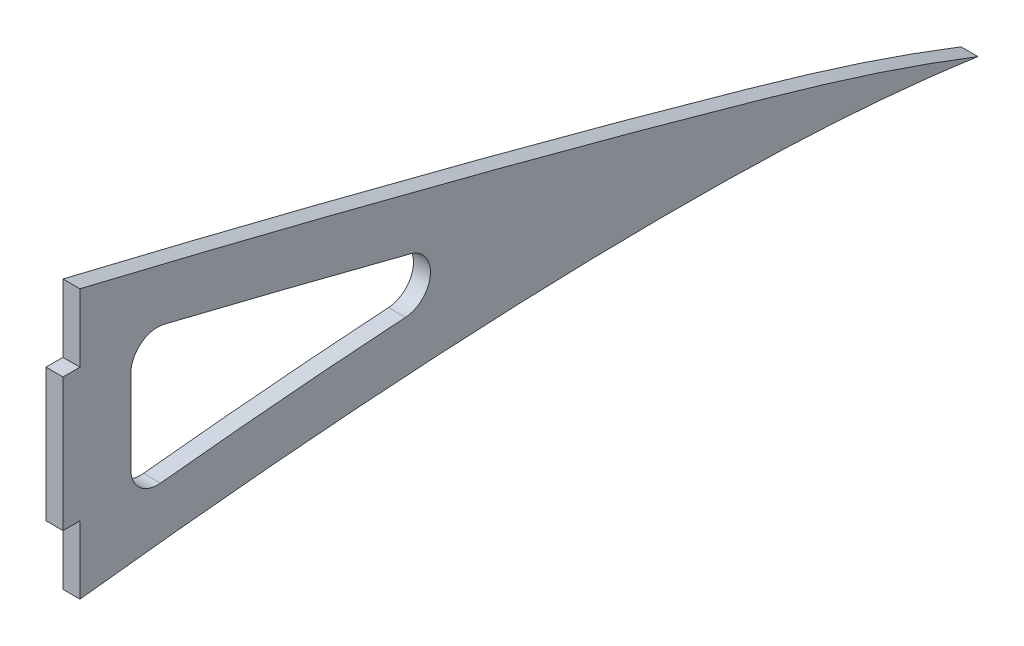
SolidWorks part; units mm, degrees
material "Balsa"
ref_plane "Front" through (0, 0, 0) normal (0, 0, 1) x (1, 0, 0)
ref_plane "Top" through (0, 0, 0) normal (0, 1, 0) x (1, 0, 0)
ref_plane "Right" through (0, 0, 0) normal (1, 0, 0) x (0, 0, -1)
sketch "Sketch1" plane through (0, 0, 0) normal (1, 0, 0) x (0, 0, -1)
  line L0 (616.0961, 24.8993) -> (616.0961, 10.6118) construction
  line L1 (616.0961, 24.8993) -> (616.0961, 10.5667)
  line L2 (612.9211, 24.8993) -> (612.9211, 10.6118) construction
  line L3 (616.0961, 10.5667) -> (612.9211, 10.5667)
  line L4 (616.0961, -14.3323) -> (612.9211, -14.3323)
  line L5 (616.0961, 23.2667) -> (616.0961, 10.5667) construction
  line L6 (616.0961, -27.0323) -> (616.0961, -14.3323)
  line L7 (612.9211, 10.5667) -> (612.9211, -14.3323)
  spline S0 degree 3 poles (304.4894, -1963.048) (904.56, -11.0089) (840.5576, -43.532) (789.3572, -23.4586) (777.0615, -18.6436) (760.5817, -13.0401) (739.9968, -7.1233) (715.5772, -0.3798) (687.647, 7.013) (656.6835, 14.9584) (623.1589, 23.2583) (587.5492, 31.6944) (550.3192, 40.0262) (511.9148, 48.0016) (472.7617, 55.3745) (433.2622, 61.9128) (393.7959, 67.4048) (354.7199, 71.6552) (316.357, 74.5357) (278.9313, 75.7536) (242.6994, 75.3938) (207.8706, 73.5467) (174.7468, 70.259) (143.6014, 65.7682) (114.7621, 60.1875) (88.5345, 53.6285) (65.199, 46.2382) (45.0006, 38.1339) (28.1586, 29.5092) (14.871, 20.5578) (6.1442, 12.3133) (1.9481, 6.1765) (0.6391, 3.0841) (0.217, 1.668) (-2.2377, -10.856) (31.8726, -26.5577) (-1993.0578, 155.2139) knots -0.166991 -0.166991 -0.166991 -0.166991 0.003802 0.014472 0.030564 0.051299 0.077028 0.107574 0.142399 0.180921 0.222525 0.266591 0.312515 0.35971 0.407632 0.455773 0.503669 0.550901 0.597096 0.641976 0.685512 0.727353 0.767354 0.805169 0.840471 0.872937 0.902335 0.928425 0.951113 0.970253 0.985871 0.993982 0.996753 0.997907 0.999293 1.04244 1.04244 1.04244 1.04244 only from (802.1511, -28.0117) to (0, 0) construction
  spline S1 degree 3 poles (802.1511, -28.0117) (801.1372, -27.7105) (797.2784, -26.5642) (789.3572, -23.4586) (777.0615, -18.6436) (760.5817, -13.0401) (739.9968, -7.1233) (715.5772, -0.3798) (687.647, 7.013) (656.6835, 14.9584) (623.1589, 23.2583) (587.5492, 31.6944) (550.3192, 40.0262) (511.9148, 48.0016) (472.7617, 55.3745) (433.2622, 61.9128) (393.7959, 67.4048) (354.7199, 71.6552) (316.357, 74.5357) (278.9313, 75.7536) (242.6994, 75.3938) (207.8706, 73.5467) (174.7468, 70.259) (143.6014, 65.7682) (114.7621, 60.1875) (88.5345, 53.6285) (65.199, 46.2382) (45.0006, 38.1339) (28.1586, 29.5092) (14.871, 20.5578) (6.1442, 12.3133) (1.9481, 6.1765) (0.6391, 3.0841) (0.217, 1.668) (0.0426, 0.7778) (0.0107, 0.1963) (0, 0) knots 0 0 0 0 0.003802 0.014472 0.030564 0.051299 0.077028 0.107574 0.142399 0.180921 0.222525 0.266591 0.312515 0.35971 0.407632 0.455773 0.503669 0.550901 0.597096 0.641976 0.685512 0.727353 0.767354 0.805169 0.840471 0.872937 0.902335 0.928425 0.951113 0.970253 0.985871 0.993982 0.996753 0.997907 0.999293 1 1 1 1
  spline S2 degree 3 poles (-1994.7901, -130.8385) (49.5083, 45.0487) (-3.9103, 18.1854) (0.5702, -4.3968) (2.5361, -10.6164) (7.9982, -20.5501) (16.1137, -34.185) (25.7513, -48.9002) (36.932, -62.9388) (49.3364, -75.9186) (65.2269, -85.625) (84.4528, -91.7174) (106.8521, -96.1515) (132.5109, -98.5722) (161.1944, -99.0924) (192.7613, -97.7042) (227.0382, -94.5118) (263.8348, -89.6638) (302.9215, -83.3884) (344.0178, -75.9778) (386.7768, -67.7807) (430.7746, -59.2023) (475.4963, -50.6638) (520.3353, -42.6036) (564.5889, -35.4228) (607.4709, -29.4733) (648.1275, -25.0145) (685.6676, -22.1862) (719.1968, -21.0048) (747.8303, -21.2786) (770.6884, -22.8547) (787.0914, -25.0735) (855.7552, -37.3672) (910.4178, -89.1553) (1388.6423, 1880.9845) knots -0.071347 -0.071347 -0.071347 -0.071347 0.001821 0.004613 0.009135 0.024676 0.044153 0.064937 0.086321 0.107138 0.1276 0.150893 0.177565 0.207668 0.241222 0.278203 0.318526 0.362031 0.408465 0.457479 0.508614 0.561296 0.614835 0.668438 0.721214 0.772202 0.820393 0.864766 0.904324 0.938132 0.965242 0.98469 0.99621 1.210002 1.210002 1.210002 1.210002 only from (0, 0) to (802.1511, -28.0117) construction
  spline S3 degree 3 poles (0, 0) (0.0175, -0.519) (0.0617, -1.8338) (0.5702, -4.3968) (2.5361, -10.6164) (7.9982, -20.5501) (16.1137, -34.185) (25.7513, -48.9002) (36.932, -62.9388) (49.3364, -75.9186) (65.2269, -85.625) (84.4528, -91.7174) (106.8521, -96.1515) (132.5109, -98.5722) (161.1944, -99.0924) (192.7613, -97.7042) (227.0382, -94.5118) (263.8348, -89.6638) (302.9215, -83.3884) (344.0178, -75.9778) (386.7768, -67.7807) (430.7746, -59.2023) (475.4963, -50.6638) (520.3353, -42.6036) (564.5889, -35.4228) (607.4709, -29.4733) (648.1275, -25.0145) (685.6676, -22.1862) (719.1968, -21.0048) (747.8303, -21.2786) (770.6884, -22.8547) (787.0914, -25.0735) (796.8423, -26.8193) (801.0977, -27.7751) (802.1511, -28.0117) knots 0 0 0 0 0.001821 0.004613 0.009135 0.024676 0.044153 0.064937 0.086321 0.107138 0.1276 0.150893 0.177565 0.207668 0.241222 0.278203 0.318526 0.362031 0.408465 0.457479 0.508614 0.561296 0.614835 0.668438 0.721214 0.772202 0.820393 0.864766 0.904324 0.938132 0.965242 0.98469 0.99621 1 1 1 1
  spline S4 degree 1 poles (784.1065, -23.1184) (1.589, -0.0169) knots 0 0 1 1 construction
  spline S5 degree 1 poles (1.589, -0.0169) (784.1065, -23.1184) knots 0 0 1 1 construction
  spline S6 degree 3 poles (784.1065, -23.1184) (780.1603, -21.5942) (772.229, -18.642) (760.1745, -14.6722) (747.9911, -11.0613) (731.6457, -6.456) (711.1768, -0.8453) (679.559, 7.4876) (651.9836, 14.4996) (624.3549, 21.2911) (606.6048, 25.5547) (576.4242, 32.5965) (537.8777, 41.1375) (487.9189, 51.0912) (437.7208, 59.724) (387.2787, 66.7289) (345.0506, 70.936) (311.1879, 73.0641) (277.2796, 74.2092) (243.3427, 73.88) (209.4764, 71.9586) (184.1438, 69.6475) (158.905, 66.4678) (133.8072, 62.3586) (108.9155, 57.1874) (88.425, 51.8354) (72.2738, 46.7811) (60.3184, 42.5401) (48.5771, 37.7737) (37.1197, 32.3878) (27.9272, 27.2538) (20.9064, 22.6554) (15.8717, 18.9075) (11.1186, 14.8241) (7.5582, 11.0807) (5.0251, 7.8349) (3.3892, 5.2955) (2.3111, 3.0614) (1.8056, 1.4859) (1.654, 0.7258) (1.6104, 0.3499) (1.5955, 0.1003) (1.589, -0.0169) knots 0.0223 0.0223 0.0223 0.0223 0.037575 0.05285 0.068125 0.083401 0.113951 0.144502 0.201029 0.216305 0.246855 0.266703 0.327804 0.388905 0.450006 0.511107 0.572208 0.602759 0.633309 0.69441 0.724961 0.755511 0.786062 0.816612 0.847162 0.877713 0.892988 0.908263 0.923539 0.938814 0.954089 0.961727 0.969364 0.977002 0.98464 0.988458 0.992277 0.996096 0.998005 0.99896 0.999438 0.999915 0.999915 0.999915 0.999915
  spline S7 degree 3 poles (1.589, -0.0169) (1.5978, -0.2781) (1.617, -0.8171) (1.6706, -1.5251) (1.7727, -2.2395) (1.9645, -3.217) (2.2822, -4.4731) (2.892, -6.4557) (3.825, -8.9127) (5.5748, -12.7649) (8.1549, -17.4947) (12.5101, -25.0363) (18.1123, -34.2943) (25.2301, -45.181) (31.6891, -53.8227) (37.2128, -60.4726) (42.9501, -66.9629) (50.6018, -74.4394) (61.3489, -81.5128) (73.1594, -86.5673) (85.641, -90.1112) (98.3223, -92.8576) (115.4237, -95.4885) (137.057, -97.1574) (163.0971, -97.3914) (189.1354, -96.2564) (215.1195, -94.0861) (241.0338, -91.1098) (275.4921, -86.3076) (318.4041, -79.1225) (369.7356, -69.4844) (421.0135, -59.4768) (472.335, -49.6151) (523.7845, -40.3589) (567.397, -33.4142) (602.5248, -28.6193) (637.1568, -24.5175) (671.3273, -21.4749) (705.604, -19.8163) (731.789, -19.4122) (758.0003, -20.1502) (775.4469, -21.8673) (784.1065, -23.1184) knots 0.000082 0.000082 0.000082 0.000082 0.001038 0.001993 0.002948 0.003903 0.005814 0.007724 0.011545 0.015366 0.023009 0.030651 0.045935 0.061219 0.076503 0.084145 0.091787 0.107071 0.122355 0.137639 0.152923 0.168208 0.183492 0.21406 0.244628 0.275196 0.305765 0.336333 0.366901 0.428038 0.489174 0.55031 0.611447 0.672583 0.73372 0.766342 0.79691 0.855993 0.886561 0.917129 0.947697 0.978266 0.978266 0.978266 0.978266
  point P8 (625.6211, 24.8993)
  point P9 (625.6211, -28.6308)
  dimension "D2" = 12.7
  dimension "D3" = 12.7
  dimension "D1" = 1.5875
extrude "Boss-Extrude1" add sketch "Sketch1" along normal mid plane 3.175 contours L6 S7 S6 L1 L3 L7 L4
sketch "Sketch3" plane through (-1.5875, 0, 0) normal (-1, 0, 0) x (0, 0, 1)
  line L8 (-616.0961, 10.5667) -> (-616.0961, -14.3323)
  line L10 (-625.6211, 10.5667) -> (-625.6211, -14.3323)
  line L12 (-625.6211, -16.3575) -> (-625.6211, -14.3323)
  line L14 (-625.6211, 10.5667) -> (-625.6211, 11.1624)
  line L22 (-616.0961, -27.0323) -> (-616.0961, -14.3323)
  line L23 (-616.0961, -14.3323) -> (-612.9211, -14.3323)
  line L24 (-612.9211, -14.3323) -> (-612.9211, 10.5667)
  line L25 (-612.9211, 10.5667) -> (-616.0961, 10.5667)
  line L26 (-616.0961, 10.5667) -> (-616.0961, 23.2667)
  line L27 (-616.0961, -27.0323) -> (-616.0961, -14.3323)
  line L31 (-616.0961, 10.5667) -> (-616.0961, 23.2667)
  spline S0 degree 1 poles (-709.5538, -10.3156) (-625.6211, -16.3575) knots 0 0 1 1 construction
  spline S1 degree 1 poles (-625.6211, 11.1624) (-709.5538, -10.3156) knots 0 0 1 1 construction
  spline S2 degree 3 poles (1634.6736, -1607.9777) (681.5883, 157.0929) (1.6305, 175.1672) (-651.9836, 14.4996) (-679.559, 7.4876) (-711.1768, -0.8453) (-731.6457, -6.456) (-747.9911, -11.0613) (-760.1745, -14.6722) (-967.9627, -83.1024) (-1104.2081, -346.6774) (-2002.5645, 2676.6356) knots -2.312001 -2.312001 -2.312001 -2.312001 0.037575 0.05285 0.109378 0.139928 0.170479 0.185754 0.201029 0.216305 0.97567 0.97567 0.97567 0.97567 only from (-616.0961, 23.2667) to (-784.1065, -23.1184)
  spline S3 degree 3 poles (-137.9126, -2890.9442) (-1254.9723, -306.121) (-1000.8122, -26.9869) (-731.789, -19.4122) (-705.604, -19.8163) (-671.3273, -21.4749) (-68.1702, -75.1819) (477.5748, -530.0036) (1018.4617, 2058.6772) knots -0.067892 -0.067892 -0.067892 -0.067892 0.812194 0.842762 0.87333 0.903899 0.962981 2.995374 2.995374 2.995374 2.995374 only from (-784.1065, -23.1184) to (-616.0961, -27.0323)
  spline S4 degree 3 poles (-616.0961, 23.2667) (-620.2246, 22.2755) (-628.4782, 20.2775) (-651.9836, 14.4996) (-679.559, 7.4876) (-711.1768, -0.8453) (-731.6457, -6.456) (-747.9911, -11.0613) (-760.1745, -14.6722) (-772.229, -18.642) (-780.1603, -21.5942) (-784.1065, -23.1184) knots 0.0223 0.0223 0.0223 0.0223 0.037575 0.05285 0.109378 0.139928 0.170479 0.185754 0.201029 0.216305 0.23158 0.23158 0.23158 0.23158
  spline S5 degree 3 poles (-784.1065, -23.1184) (-775.4469, -21.8673) (-758.0003, -20.1502) (-731.789, -19.4122) (-705.604, -19.8163) (-671.3273, -21.4749) (-641.5011, -24.1307) (-620.4251, -26.521) (-616.0961, -27.0323) knots 0.781626 0.781626 0.781626 0.781626 0.812194 0.842762 0.87333 0.903899 0.962981 0.978266 0.978266 0.978266 0.978266
  spline S6 degree 3 poles (-625.6211, -16.3575) (-632.5784, -15.5905) (-646.4983, -14.1649) (-667.4549, -12.4003) (-688.4629, -11.0653) (-702.5252, -10.5017) (-709.5538, -10.3156) knots 0.868429 0.868429 0.868429 0.868429 0.89278 0.917131 0.941482 0.965833 0.965833 0.965833 0.965833
  spline S7 degree 3 poles (-709.5538, -10.3156) (-702.5861, -8.44) (-688.6403, -4.7502) (-667.6567, 0.6772) (-646.6553, 5.9905) (-632.636, 9.4525) (-625.6211, 11.1624) knots 0.036835 0.036835 0.036835 0.036835 0.062877 0.088919 0.114961 0.141003 0.141003 0.141003 0.141003
  dimension "D1" = 0
  dimension "D2" = 9.525
extrude "Cut-Extrude2" cut sketch "Sketch3" against normal through all both and the other way through all contours S7 S6 L12 L10 L14
fillet "Fillet2" radius 5 3 edges at (0, 11.1624, -625.6211) (0, -16.3575, -625.6211) (0, -10.3156, -709.5538)
